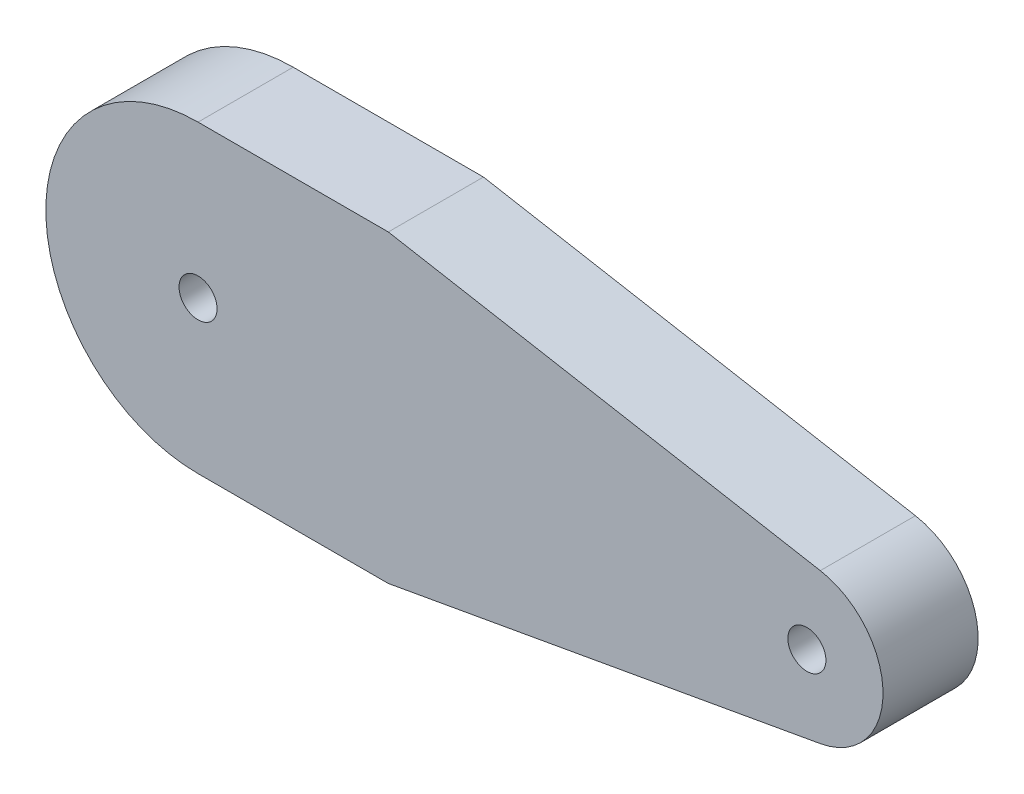
SolidWorks part; units mm, degrees
ref_plane "Front Plane" through (0, 0, 0) normal (0, 0, 1) x (1, 0, 0)
ref_plane "Top Plane" through (0, 0, 0) normal (0, 1, 0) x (1, 0, 0)
ref_plane "Right Plane" through (0, 0, 0) normal (1, 0, 0) x (0, 0, -1)
sketch "Sketch1" plane through (0, 0, 0) normal (0, 0, 1) x (1, 0, 0)
  line L0 (0, 0) -> (320, 0) construction
  line L1 (0, 80) -> (100, 80)
  line L2 (0, -80) -> (100, -80)
  line L3 (100, 80) -> (327.0453, 39.3747)
  line L4 (100, -80) -> (327.0453, -39.3747)
  arc A0 (0, 80) -> (0, -80) centre (0, 0) ccw
  arc A1 (327.0453, -39.3747) -> (327.0453, 39.3747) centre (320, 0) ccw
  dimension "D1" = 80
  dimension "D2" = 40
  dimension "D3" = 100
  dimension "D4" = 320
extrude "Boss-Extrude1" add sketch "Sketch1" along normal blind 50
sketch "Sketch2" plane through (0, 0, 50) normal (0, 0, 1) x (1, 0, 0)
  circle A0 centre (0, 0) radius 10
  circle A1 centre (320, 0) radius 10
  arc A2 (327.0453, -39.3747) -> (327.0453, 39.3747) centre (320, 0) ccw construction
  dimension "D1" = 20
extrude "Cut-Extrude1" cut sketch "Sketch2" against normal blind 20
sketch "Sketch3" plane through (0, 0, 0) normal (0, 1, 0) x (1, 0, 0)
  line L0 (320, -75) -> (320, -223.9922) construction
  line L1 (320, -75) -> (468.9922, -75) construction
  text T0 "Z2" font "Century Gothic" height 20
  text T1 "X2" font "Century Gothic" height 20
  point P2 (320, -102.6222)
  point P4 (419.8143, -112.4606)
  point P5 (314.1412, -75)
  point P7 (0, 0)
  point P8 (320, -81.1784)
  dimension "D1" = 320
  dimension "D2" = 75
ref_plane "Plane1" through (0, 0, 75) normal (0, 0, 1) x (1, 0, 0)
sketch "Sketch4" plane through (0, 0, 75) normal (0, 0, 1) x (1, 0, 0)
  line L0 (320, 0) -> (320, 148.9922) construction
  line L1 (320, 0) -> (468.9922, 0) construction
  text T0 "Y2" font "Century Gothic" height 20
  point P6 (312.5869, 0)
